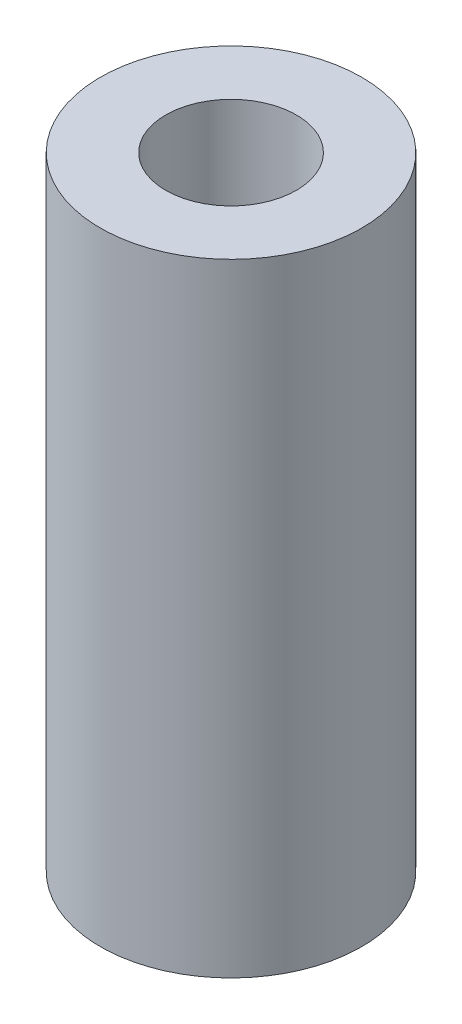
SolidWorks part; units mm, degrees
material "Acrylic (Medium-high impact)"
ref_plane "Front Plane" through (0, 0, 0) normal (0, 0, 1) x (1, 0, 0)
ref_plane "Top Plane" through (0, 0, 0) normal (0, 1, 0) x (1, 0, 0)
ref_plane "Right Plane" through (0, 0, 0) normal (1, 0, 0) x (0, 0, -1)
sketch "Sketch2" plane through (0, 0, 0) normal (0, 1, 0) x (1, 0, 0)
  circle A0 centre (0, 0) radius 4
  dimension "D1" = 8
extrude "Boss-Extrude2" add sketch "Sketch2" along normal mid plane 19.05
sketch "Sketch3" plane through (0, 9.525, 0) normal (0, 1, 0) x (1, 0, 0)
  circle A0 centre (0, 0) radius 2
  dimension "D1" = 4
extrude "Cut-Extrude1" cut sketch "Sketch3" against normal blind 6.35
mirror "Mirror1" about plane through (0, 0, 0) normal (0, 1, 0) of "Cut-Extrude1"
